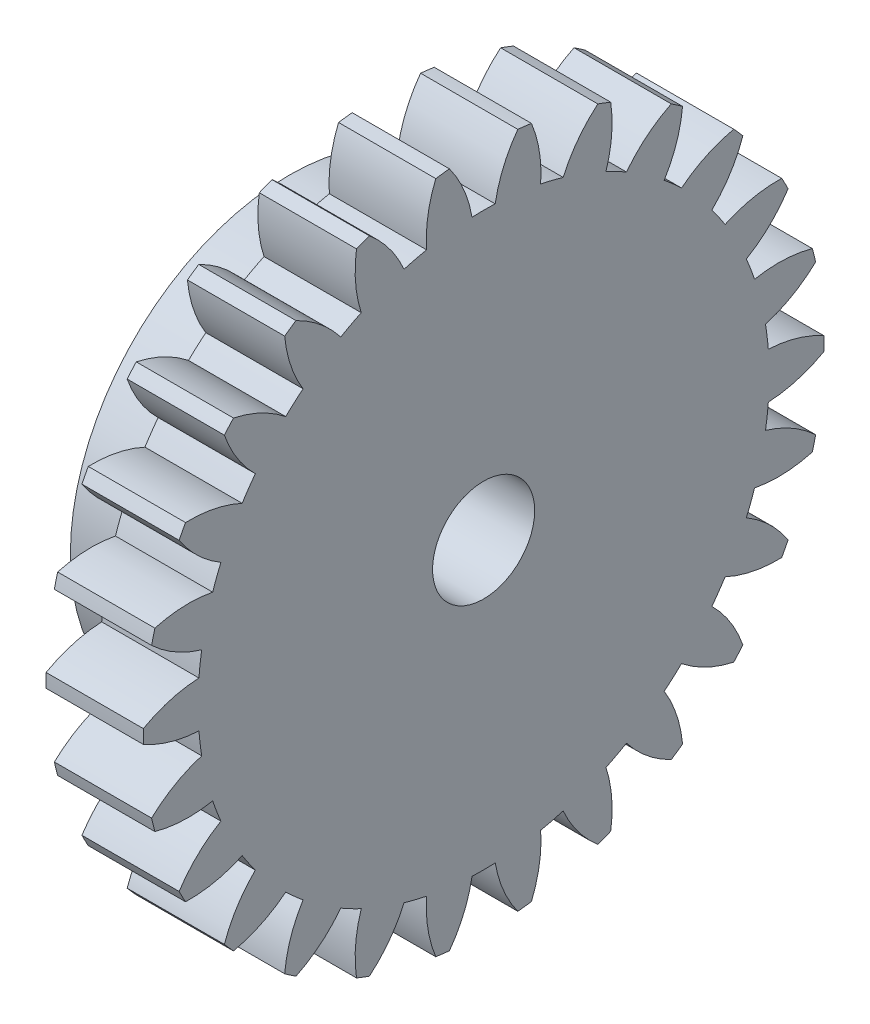
SolidWorks part; units mm, degrees
ref_plane "Plane1" through (0, 0, 0) normal (0, 0, 1) x (1, 0, 0)
ref_plane "Plane2" through (0, 0, 0) normal (0, 1, 0) x (1, 0, 0)
ref_plane "Plane3" through (0, 0, 0) normal (1, 0, 0) x (0, 0, -1)
other "Configuration Table"
sketch "HoldingSke" plane through (0, 0, 0) normal (0, 1, 0) x (1, 0, 0)
  line L0 (0, 0) -> (0.8988, -0.4384)
  line L1 (-15, 0) -> (100, 0) construction
  line L2 (0, 0) -> (-2.1039, 2.3779)
  line L3 (0, 0) -> (-11.863, 4.5341)
  line L4 (0, 0) -> (7.762, 3.7858)
  line L5 (0, 0) -> (-46.8476, -17.4728)
  line L6 (0, 0) -> (-3.3159, -2.2372)
  line L7 (-2.1039, 2.3779) -> (8.6586, 51.2059)
  line L8 (-76.2, 54.61) -> (-75.5, 54.61)
  line L9 (-71.009, 38.7566) -> (-53.1078, 45.2721)
  line L10 (-76.2, 71.12) -> (104.1128, 71.12)
  line L11 (0, 0) -> (-4, 0)
  line L12 (-76.2, 101.6) -> (-76.162, 101.6)
  line L13 (24.9733, 27.94) -> (52.9518, 28.4284)
  line L14 (24.9733, 27.94) -> (24.9743, 27.94)
  line L15 (24.9733, 27.94) -> (100.4006, 29.5858)
  line L16 (-63.627, -1) -> (-12.827, -1)
  circle A0 centre (0, 0) radius 2
  circle A1 centre (0, 0) radius 11.749
  circle A2 centre (0, 0) radius 37.5
  circle A3 centre (0, 0) radius 2
  dimension "MHD" = 23.498
  dimension "Hub_dia" = 75
  dimension "Bore" = 4
  dimension "MBD" = 4
  dimension "Num_teeth" = 26
  dimension "Pitch" = 1
  dimension "Overall_len" = 50
  dimension "Show_teeth" = 26
  dimension "Thickness" = 4
  dimension "OAL" = 50.0001
  dimension "T_dim" = 0.7
  dimension "Ap" = 20
  dimension "H" = 19.05
  dimension "Pitch_radius" = 180.3128
  dimension "Width" = 4
  dimension "Backlash" = 0.038
  dimension "Addendum_fac" = 1
  dimension "Dedendum_fac" = 1.25
  dimension "Clearance_fac" = 0.25
  dimension "Dedendum_add" = 0.001
  dimension "Module" = 1
sketch "BasProSke" plane through (0, 0, 0) normal (0, 1, 0) x (1, 0, 0)
  line L0 (-10, 0) -> (60, 0) construction
  line L1 (0, 0) -> (0, 14)
  line L2 (0, 0) -> (4, 0)
  line L3 (4, 0) -> (4, 14)
  line L4 (4, 14) -> (0, 14)
  dimension "Thickness" = 4
  dimension "Diameter" = 28
revolve "Base-Revolve" add sketch "BasProSke" angle 360 about L0
sketch "TooCutSke" plane through (0, 0, 0) normal (1, 0, 0) x (0, 0, -1)
  line L1 (0, 0) -> (0, 107) construction
  line L2 (0, 0) -> (-0.8514, 12.9721) construction
  line L3 (0, 0) -> (-3.1292, 25.771) construction
  line L4 (-0.8514, 12.9721) -> (-1.5646, 12.8855) construction
  arc A0 (0.477, 11.7393) -> (-0.477, 11.7393) centre (0, 0) ccw
  arc A1 (1.4241, 13.9529) -> (-1.4241, 13.9529) centre (0, 0) ccw
  circle A2 centre (0, 0) radius 13 construction
  circle A3 centre (0, 0) radius 12.216 construction
  arc A4 (-0.477, 11.7393) -> (-1.4241, 13.9529) centre (-5.6014, 10.8561) ccw
  arc A5 (1.4241, 13.9529) -> (0.477, 11.7393) centre (5.6014, 10.8561) ccw
  dimension "Root_dia" = 23.498
  dimension "Overcut_dia" = 28.0508
  dimension "Pitch_dia" = 26
  dimension "Base_dia" = 24.432
  dimension "Flank_rad" = 5.2
  dimension "Half_ang" = 6.923
  dimension "Half_CT" = 0.7184
extrude "ToothCut" cut sketch "TooCutSke" along normal through all
fillet "Breaks" [suppressed] radius 0.02
fillet "RootFillets" [suppressed] radius 0.251
pattern_circular "TeethCuts" count 26 every 13.846 about axis through (-10, 0, 0) along (1, 0, 0) of "ToothCut", "RootFillets", "Breaks"
sketch "HubNeaOneSke" plane through (0, 0, 0) normal (-1, 0, 0) x (0, 0, 1)
  circle A0 centre (0, 0) radius 11.749
  dimension "Diameter" = 23.498
extrude "HubNearOne" [suppressed] add sketch "HubNeaOneSke" along normal blind 46.0001
sketch "HubNeaBotSke" plane through (0, 0, 0) normal (-1, 0, 0) x (0, 0, 1)
  circle A0 centre (0, 0) radius 11.749
  dimension "Diameter" = 23.498
extrude "HubNearBoth" [suppressed] add sketch "HubNeaBotSke" along normal blind 23
ref_plane "FarPln" through (4, 0, 0) normal (1, 0, 0) x (0, 0, -1)
sketch "HubFarSke" plane through (4, 0, 0) normal (1, 0, 0) x (0, 0, -1)
  circle A0 centre (0, 0) radius 11.749
  dimension "Diameter" = 23.498
extrude "HubFar" [suppressed] add sketch "HubFarSke" along normal blind 23
sketch "BorSke" plane through (0, 0, 0) normal (1, 0, 0) x (0, 0, -1)
  circle A0 centre (0, 0) radius 2
  dimension "Diameter" = 4
extrude "Bore" cut sketch "BorSke" along normal mid plane 100.0001
sketch "KeySke" plane through (0, 0, 0) normal (1, 0, 0) x (0, 0, -1)
  line L0 (-0.8, 0) -> (-0.8, 2.7)
  line L1 (-0.8, 2.7) -> (0.8, 2.7)
  line L2 (0.8, 2.7) -> (0.8, 0)
  line L3 (0, 0) -> (0, 34) construction
  line L4 (-0.8, 0) -> (0.8, 0)
  dimension "Offset" = 2.7
  dimension "Width" = 1.6
extrude "Keyway" [suppressed] cut sketch "KeySke" along normal mid plane 100.0001
pattern_circular "Keyway2" [suppressed] count 2 every 90 about axis through (-10, 0, 0) along (1, 0, 0)
sketch "草图1" plane through (0, 0, 0) normal (-1, 0, 0) x (0, 0, 1)
  circle A0 centre (0, 0) radius 9
  circle A1 centre (0, 0) radius 2
  dimension "D1" = 4
  dimension "D2" = 18
extrude "凸台-拉伸1" add sketch "草图1" along normal blind 4
sketch "草图2" plane through (-4, 0, 0) normal (-1, 0, 0) x (0, 0, 1)
  line L1 (6.2, 3.5796) -> (0, 7.1591)
  line L2 (0, 7.1591) -> (-6.2, 3.5796)
  line L3 (-6.2, 3.5796) -> (-6.2, -3.5796)
  line L4 (-6.2, -3.5796) -> (0, -7.1591)
  line L5 (0, -7.1591) -> (6.2, -3.5796)
  line L6 (6.2, -3.5796) -> (6.2, 3.5796)
  circle A0 centre (0, 0) radius 6.2 construction
  dimension "D1" = 12.4
extrude "切除-拉伸1" cut sketch "草图2" against normal blind 3
sketch "草图3" plane through (4, 0, 0) normal (1, 0, 0) x (0, 0, -1)
  point P0 (0, 0)
sketch "草图4" plane through (4, 0, 0) normal (1, 0, 0) x (0, 0, -1)
  circle A0 centre (0, 0) radius 2.1
  dimension "D1" = 4.2
extrude "切除-拉伸2" cut sketch "草图4" against normal through all
equation "' \"Module@HoldingSke\" = 6.35"
equation "' \"Num_teeth@HoldingSke\" = 12"
equation "' \"Ap@HoldingSke\" =  20"
equation "' \"Ap@HoldingSke\" = 20"
equation "' \"Width@HoldingSke\" = 0.5 * 25.4"
equation "' \"Hub_dia@HoldingSke\"= 1 * 25.4"
equation "' \"Hub_dia@HoldingSke\" = 1 * 25.4"
equation "' \"Overall_len@HoldingSke\" = 1.0 * 25.4"
equation "' \"Bore@HoldingSke\" = 0.75 * 25.4"
equation "' \"T_dim@HoldingSke\" = 0.1 * 25.4"
equation "' \"Width@KeySke\" = 0.25 * 25.4"
equation "' \"Show_teeth@HoldingSke\" = 13"
equation "' \"Backlash@HoldingSke\" = 0.009 * 25.4"
equation "' \"Addendum_fac@HoldingSke\" = 1.0"
equation "' \"Dedendum_fac@HoldingSke\" = 1.25"
equation "' \"Dedendum_add@HoldingSke\" = 0.00005 * 25.4"
equation "' \"Clearance_fac@HoldingSke\" = 0.25"
equation "\"Pitch@HoldingSke\" = 1 / \"Module@HoldingSke\""
equation "\"Overcut_dia@TooCutSke\" = (\"Num_teeth@HoldingSke\" + 2 * \"Addendum_fac@HoldingSke\") / \"Pitch@HoldingSke\" + 0.002 * 25.4"
equation "\"Pitch_dia@TooCutSke\" = \"Num_teeth@HoldingSke\" / \"Pitch@HoldingSke\""
equation "\"Base_dia@TooCutSke\" = \"Num_teeth@HoldingSke\" / \"Pitch@HoldingSke\" * cos((\"Ap@HoldingSke\"  * 3.14159265 / 180))"
equation "\"Root_dia@TooCutSke\" = (\"Num_teeth@HoldingSke\" + 2) / \"Pitch@HoldingSke\" - 2 * (\"Addendum_fac@HoldingSke\" + \"Dedendum_fac@HoldingSke\") / \"Pitch@HoldingSke\" - \"Dedendum_add@HoldingSke\" * 2"
equation "\"Half_ang@TooCutSke\" = 180 / \"Num_teeth@HoldingSke\""
equation "\"Half_CT@TooCutSke\" = \"Num_teeth@HoldingSke\" / \"Pitch@HoldingSke\" * sin((3.14159265 / 2 / \"Num_teeth@HoldingSke\")) / 2 - 7 * \"Backlash@HoldingSke\" / 4"
equation "\"Flank_rad@TooCutSke\" = \"Num_teeth@HoldingSke\" / \"Pitch@HoldingSke\" / 5"
equation "\"Radius@RootFillets\" = \"Clearance_fac@HoldingSke\" / \"Pitch@HoldingSke\" + \"Dedendum_add@HoldingSke\""
equation "\"Break_rad@Breaks\" = 0.02 / \"Pitch@HoldingSke\""
equation "\"Thickness@HoldingSke\" = \"Width@HoldingSke\""
equation "\"OAL@HoldingSke\" = \"Thickness@HoldingSke\""
equation "\"MHD@HoldingSke\" = (\"Num_teeth@HoldingSke\" + 2) / \"Pitch@HoldingSke\" - 2 * (\"Addendum_fac@HoldingSke\" + \"Dedendum_fac@HoldingSke\")  / \"Pitch@HoldingSke\" - \"Dedendum_add@HoldingSke\" * 2"
equation "\"MBD@HoldingSke\" = (\"Num_teeth@HoldingSke\" + 2) / \"Pitch@HoldingSke\" - 2 * (\"Addendum_fac@HoldingSke\" + \"Dedendum_fac@HoldingSke\")  / \"Pitch@HoldingSke\" - \"Dedendum_add@HoldingSke\" * 2 - 0.002 * 25.4"
equation "\"MHD@HoldingSke\" = ((sgn( \"MHD@HoldingSke\" - \"Hub_dia@HoldingSke\" )-1)*( \"MHD@HoldingSke\" - \"Hub_dia@HoldingSke\" ))/-2+ \"Hub_dia@HoldingSke\""
equation "\"MBD@HoldingSke\" = ((sgn( \"MBD@HoldingSke\" - \"Bore@HoldingSke\" )-1)*( \"MBD@HoldingSke\" - \"Bore@HoldingSke\" ))/-2+ \"Bore@HoldingSke\""
equation "\"OAL@HoldingSke\" = ((sgn( \"OAL@HoldingSke\" - \"Overall_len@HoldingSke\" )+1)*( \"OAL@HoldingSke\" - \"Overall_len@HoldingSke\" ))/2 + \"Overall_len@HoldingSke\" + 0.000002 * 25.4"
equation "\"Num_teeth@TeethCuts\" = int( \"Show_teeth@HoldingSke\" ) + 1"
equation "\"Num_teeth@TeethCuts\" = ((sgn( \"Num_teeth@TeethCuts\" - \"Num_teeth@HoldingSke\" )-1)*( \"Num_teeth@TeethCuts\" - \"Num_teeth@HoldingSke\" ))/-2+ \"Num_teeth@HoldingSke\""
equation "\"Num_teeth@TeethCuts\" = ((sgn( \"Num_teeth@TeethCuts\" - 2.0)+1)*( \"Num_teeth@TeethCuts\" - 2.0))/2 +2.0"
equation "\"Angle@TeethCuts\" = 360.0 / \"Num_teeth@HoldingSke\""
equation "\"Diameter@BasProSke\" = (\"Num_teeth@HoldingSke\" + 2 * \"Addendum_fac@HoldingSke\") / \"Pitch@HoldingSke\""
equation "\"Thickness@BasProSke\"  = \"Thickness@HoldingSke\""
equation "' \"Fillet_rad@BasProSke\" =  \"Thickness@HoldingSke\" * 0.05"
equation "' \"Fillet_rad@BasProSke\" = \"Thickness@HoldingSke\" * 0.05"
equation "\"MHD@HoldingSke\" = ((sgn( \"MHD@HoldingSke\" - \"Root_dia@TooCutSke\" )-1)*( \"MHD@HoldingSke\" - \"Root_dia@TooCutSke\" ))/-2+ \"Root_dia@TooCutSke\""
equation "\"Diameter@HubNeaOneSke\" = \"MHD@HoldingSke\""
equation "\"Length@HubNearOne\" = \"OAL@HoldingSke\" - \"Thickness@BasProSke\""
equation "\"Diameter@HubNeaBotSke\" = \"MHD@HoldingSke\""
equation "\"Length@HubNearBoth\" = ( \"OAL@HoldingSke\" - \"Thickness@BasProSke\" ) / 2.0"
equation "\"Thickness@FarPln\" = \"Thickness@BasProSke\""
equation "\"Diameter@HubFarSke\" = \"MHD@HoldingSke\""
equation "\"Length@HubFar\" = ( \"OAL@HoldingSke\" - \"Thickness@BasProSke\" ) / 2.0"
equation "\"Diameter@BorSke\" = \"MBD@HoldingSke\""
equation "\"D1@Bore\" = \"OAL@HoldingSke\" * 2.0"
equation "\"D1@Keyway\" = \"OAL@HoldingSke\" * 2.0"
equation "\"Offset@KeySke\" = \"T_dim@HoldingSke\" + \"MBD@HoldingSke\" / 2.0"
